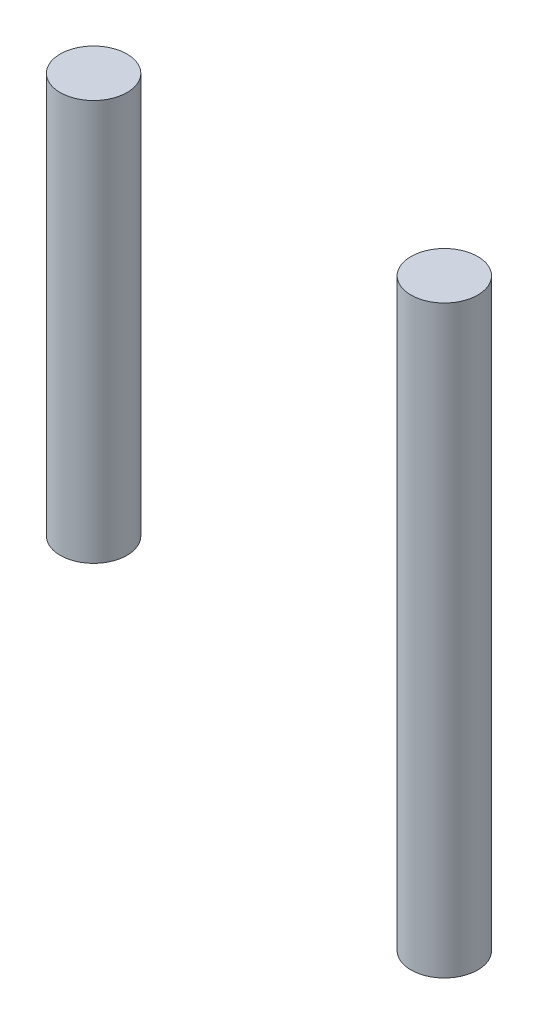
SolidWorks part; units mm, degrees
ref_plane "Front Plane" through (0, 0, 0) normal (0, 0, 1) x (1, 0, 0)
ref_plane "Top Plane" through (0, 0, 0) normal (0, 1, 0) x (1, 0, 0)
ref_plane "Right Plane" through (0, 0, 0) normal (1, 0, 0) x (0, 0, -1)
ref_plane "Plane1" through (0, -120.5, 0) normal (0, 1, 0) x (1, 0, 0)
sketch "Sketch1" plane through (0, -120.5, 0) normal (0, 1, 0) x (1, 0, 0)
  circle A0 centre (-10.5, -26) radius 2
extrude "Boss-Extrude1" add sketch "Sketch1" along normal blind 24
ref_plane "Plane2" through (0, -131.5, 0) normal (0, 1, 0) x (1, 0, 0)
sketch "Sketch2" plane through (0, -131.5, 0) normal (0, 1, 0) x (1, 0, 0)
  circle A0 centre (10.5, -26) radius 2
extrude "Boss-Extrude2" add sketch "Sketch2" along normal blind 35
